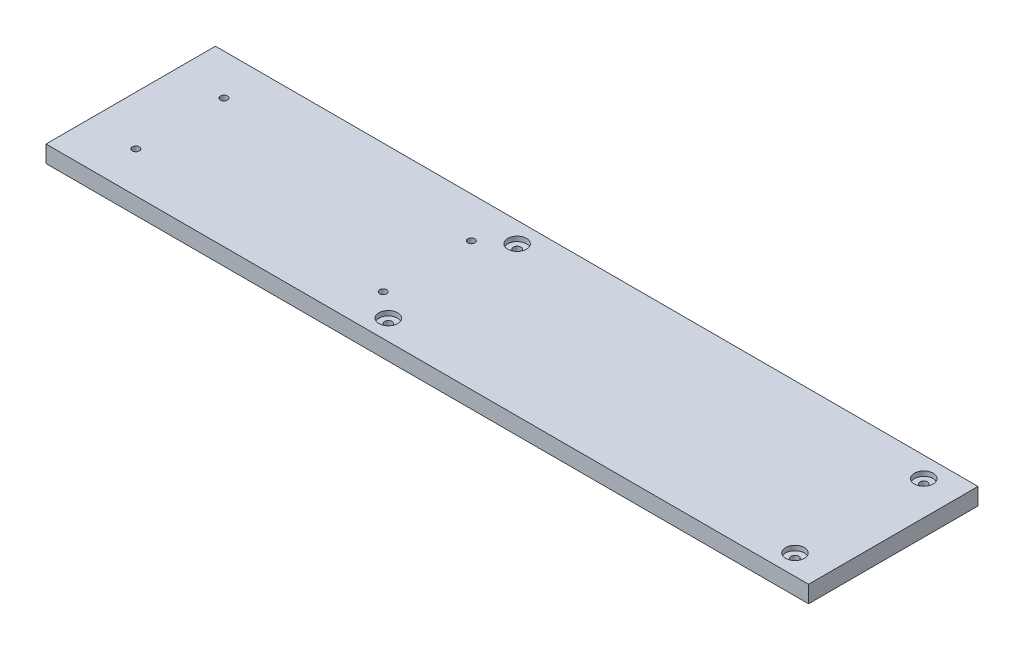
SolidWorks part; units mm, degrees
ref_plane "Front Plane" through (0, 0, 0) normal (0, 0, 1) x (1, 0, 0)
ref_plane "Top Plane" through (0, 0, 0) normal (0, 1, 0) x (1, 0, 0)
ref_plane "Right Plane" through (0, 0, 0) normal (1, 0, 0) x (0, 0, -1)
sketch "Sketch1" plane through (0, 0, 0) normal (0, 1, 0) x (1, 0, 0)
  line L1 (-225, 50) -> (225, 50)
  line L2 (-225, 50) -> (-225, -50)
  line L3 (-225, -50) -> (225, -50)
  line L4 (225, 50) -> (225, -50)
  line L5 (-225, 50) -> (225, -50) construction
  line L6 (-225, -50) -> (225, 50) construction
  point P0 (0, 0)
  dimension "D1" = 450
  dimension "D2" = 100
extrude "Boss-Extrude1" add sketch "Sketch1" along normal blind 10
hole_wizard "CBORE for M4 Hex Head Cap Screw1" positions "Sketch3" profile "Sketch4" counterbore size "M4" standard "ISO" end condition through all
sketch "Sketch3" plane through (0, 10, 0) normal (0, 1, 0) x (1, 0, 0)
  line L0 (225, -50) -> (225, 50) construction
  point P0 (205, -38)
  point P6 (205, 38)
  point P8 (-35, 38)
  point P10 (-35, -38)
  dimension "D1" = 240
  dimension "D2" = 20
  dimension "D3" = 76
  dimension "D4" = 38
sketch "Sketch4" plane through (205, 10, 38) normal (1, 0, 0) x (0, 0, 1)
  line L0 (0, 0) -> (0, 10)
  line L1 (0, 10) -> (2.25, 10)
  line L3 (2.25, 10) -> (2.25, 2.8)
  line L4 (2.25, 2.8) -> (5.5415, 2.8)
  line L5 (5.5415, 2.8) -> (5.5415, 0)
  line L7 (5.5415, 0) -> (0, 0)
  line L11 (0, -6.35) -> (0, 107.95) construction
  dimension "Thru Hole Dia." = 4.5
  dimension "Thru Hole Depth" = 10
  dimension "C'Bore Dia." = 11.083
  dimension "C'Bore Depth" = 2.8
hole_wizard "M5 Tapped Hole1" positions "Sketch5" profile "Sketch6" tap size "M5" standard "ISO" end condition through all
sketch "Sketch5" plane through (0, 10, 0) normal (0, 1, 0) x (1, 0, 0)
  point P0 (-50, 26)
  point P2 (-50, -26)
  point P4 (-196, -26)
  point P6 (-196, 26)
  point P9 (0, 0)
  point P10 (0, 0)
  point P11 (0, 0)
  point P12 (0, 0)
  dimension "D1" = 146
  dimension "D2" = 50
  dimension "D3" = 52
  dimension "D4" = 26
sketch "Sketch6" plane through (-50, 10, -26) normal (1, 0, 0) x (0, 0, 1)
  line L0 (0, 0) -> (0, 10)
  line L1 (0, 10) -> (2.1, 10)
  line L2 (2.1, 10) -> (2.1, 0)
  line L5 (2.1, 0) -> (0, 0)
  line L11 (0, -6.35) -> (0, 107.95) construction
  dimension "Thru Tap Drill Dia." = 4.2
  dimension "Thru Tap Drill Depth" = 10
cosmetic thread "Hole Thread1"
cosmetic thread "Hole Thread2"
cosmetic thread "Hole Thread3"
cosmetic thread "Hole Thread4"
